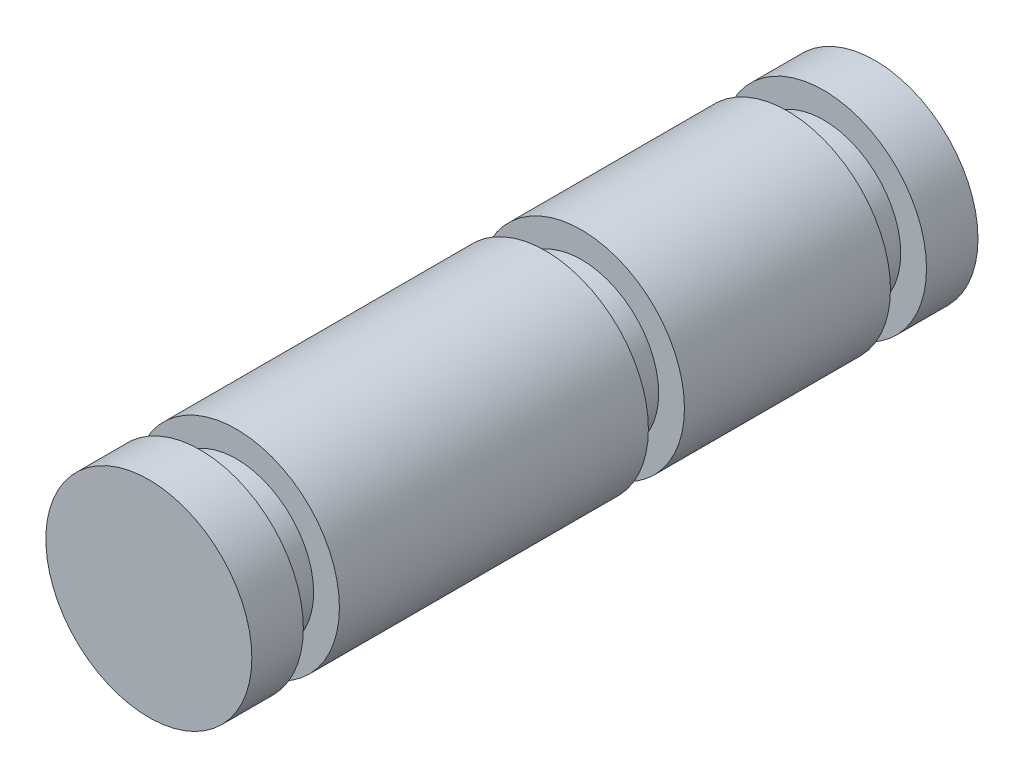
SolidWorks part; units mm, degrees
ref_plane "Plano frontal" through (0, 0, 0) normal (0, 0, 1) x (1, 0, 0)
ref_plane "Plano superior" through (0, 0, 0) normal (0, 1, 0) x (1, 0, 0)
ref_plane "Plano direito" through (0, 0, 0) normal (1, 0, 0) x (0, 0, -1)
sketch "Esboço1" plane through (0, 0, 0) normal (0, 0, 1) x (1, 0, 0)
  circle A0 centre (0, 0) radius 2
  dimension "D1" = 4
extrude "Ressalto-extrusão1" add sketch "Esboço1" along normal blind 1
sketch "Esboço2" plane through (0, 0, 1) normal (0, 0, 1) x (1, 0, 0)
  circle A0 centre (0, 0) radius 1.5
  dimension "D1" = 3
extrude "Ressalto-extrusão2" add sketch "Esboço2" along normal blind 0.7
sketch "Esboço3" plane through (0, 0, 1.7) normal (0, 0, 1) x (1, 0, 0)
  circle A0 centre (0, 0) radius 2 construction
  circle A1 centre (0, 0) radius 2
extrude "Ressalto-extrusão3" add sketch "Esboço3" along normal blind 4
sketch "Esboço4" plane through (0, 0, 5.7) normal (0, 0, 1) x (1, 0, 0)
  circle A0 centre (0, 0) radius 1.5 construction
  circle A1 centre (0, 0) radius 1.5
extrude "Ressalto-extrusão4" add sketch "Esboço4" along normal blind 0.7
sketch "Esboço5" plane through (0, 0, 6.4) normal (0, 0, 1) x (1, 0, 0)
  circle A0 centre (0, 0) radius 2 construction
  circle A1 centre (0, 0) radius 2
extrude "Ressalto-extrusão5" add sketch "Esboço5" along normal blind 6
sketch "Esboço6" plane through (0, 0, 12.4) normal (0, 0, 1) x (1, 0, 0)
  circle A0 centre (0, 0) radius 1.5 construction
  circle A1 centre (0, 0) radius 1.5
extrude "Ressalto-extrusão6" add sketch "Esboço6" along normal blind 0.7
sketch "Esboço7" plane through (0, 0, 13.1) normal (0, 0, 1) x (1, 0, 0)
  circle A0 centre (0, 0) radius 2 construction
  circle A1 centre (0, 0) radius 2
extrude "Ressalto-extrusão7" add sketch "Esboço7" along normal blind 1
